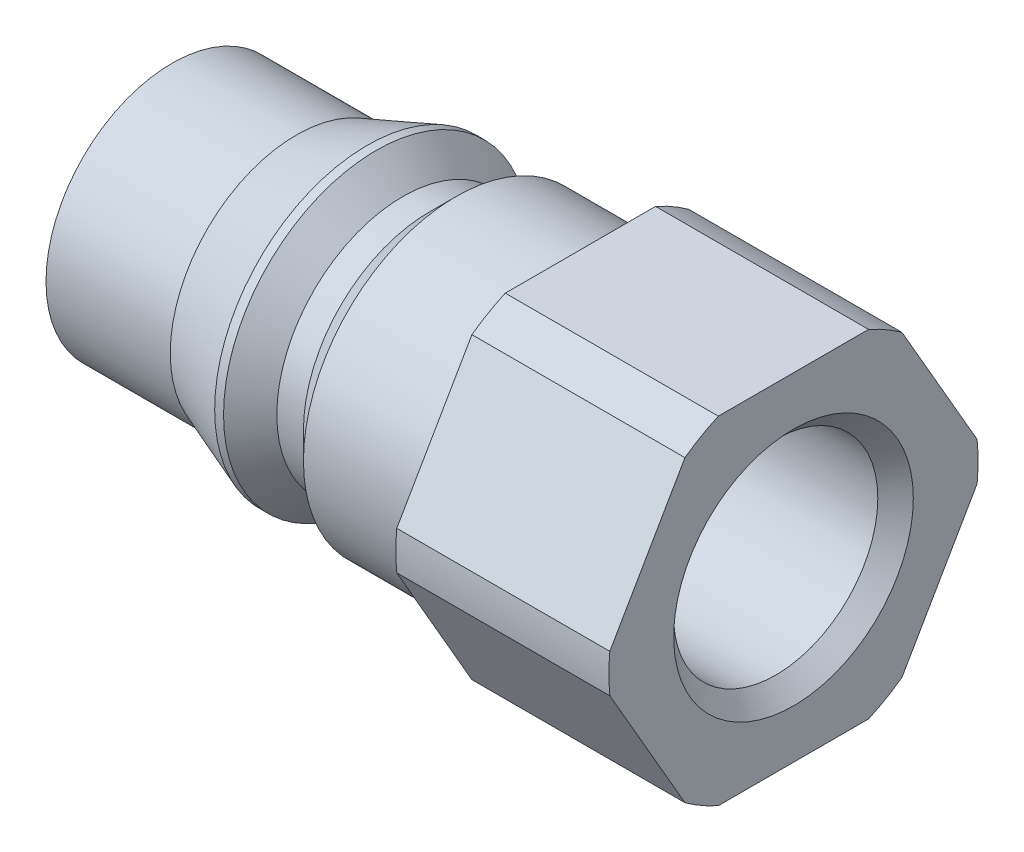
SolidWorks part; units mm, degrees
material "A286, generico"
ref_plane "Front Plane" through (0, 0, 0) normal (0, 0, 1) x (1, 0, 0)
ref_plane "Top Plane" through (0, 0, 0) normal (0, 1, 0) x (1, 0, 0)
ref_plane "Right Plane" through (0, 0, 0) normal (1, 0, 0) x (0, 0, -1)
sketch "Sketch1" plane through (0, 0, 0) normal (0, 0, 1) x (1, 0, 0)
  line L0 (0, -7.1) -> (7, -7.1)
  line L4 (13, -7.1) -> (14.5, -7.1)
  line L5 (14.5, -7.1) -> (16, -8.6)
  line L7 (35, -10.4) -> (35, -3.175)
  line L8 (35, -3.175) -> (0, -3.175)
  line L12 (0, -3.175) -> (0, -7.1)
  line L13 (0, 0) -> (35, 0) construction
  line L14 (7, -7.1) -> (11, -8.6)
  line L15 (11, -8.6) -> (11.5, -8.6)
  line L16 (11.5, -8.6) -> (13, -7.1)
  line L17 (16, -8.6) -> (23, -8.6)
  line L18 (23, -8.6) -> (23, -10.4)
  line L19 (23, -10.4) -> (35, -10.4)
  dimension "D1" = 35
  dimension "D2" = 6.35
  dimension "D3" = 14.2
  dimension "D4" = 20.8
  dimension "D5" = 45
  dimension "D6" = 45
  dimension "D7" = 1.5
  dimension "D8" = 4
  dimension "D9" = 0.5
  dimension "D10" = 1.5
  dimension "D11" = 12
  dimension "D12" = 7
revolve "Revolve1" add sketch "Sketch1" angle 360 about L13
sketch "Sketch2" plane through (35, 0, 0) normal (1, 0, 0) x (0, 0, -1)
  line L1 (-5.4848, 9.5) -> (-10.9697, 0)
  line L2 (-10.9697, 0) -> (-5.4848, -9.5)
  line L3 (-5.4848, -9.5) -> (5.4848, -9.5)
  line L4 (5.4848, -9.5) -> (10.9697, 0)
  line L5 (10.9697, 0) -> (5.4848, 9.5)
  line L6 (5.4848, 9.5) -> (-5.4848, 9.5)
  circle A0 centre (0, 0) radius 9.5 construction
  circle A1 centre (0, 0) radius 10.4 construction
  circle A2 centre (0, 0) radius 10.4
  circle M8 centre (0, 0) radius 10.4
  dimension "D1" = 19
extrude "Cut-Extrude1" cut sketch "Sketch2" against normal through all contours L6 M8 | L1 M8 | L2 M8 | L5 M8 | L4 M8 | L3 M8 | A2
sketch "Schizzo1" plane through (35, 0, 0) normal (1, 0, 0) x (0, 0, -1)
  circle A0 centre (0, 0) radius 5.75
  dimension "D1" = 11.5
extrude "Taglio-Estrusione1" cut sketch "Schizzo1" against normal blind 10
chamfer "Smusso1" distance 1 angle 45 1 edges at (35, 0, -5.75)
